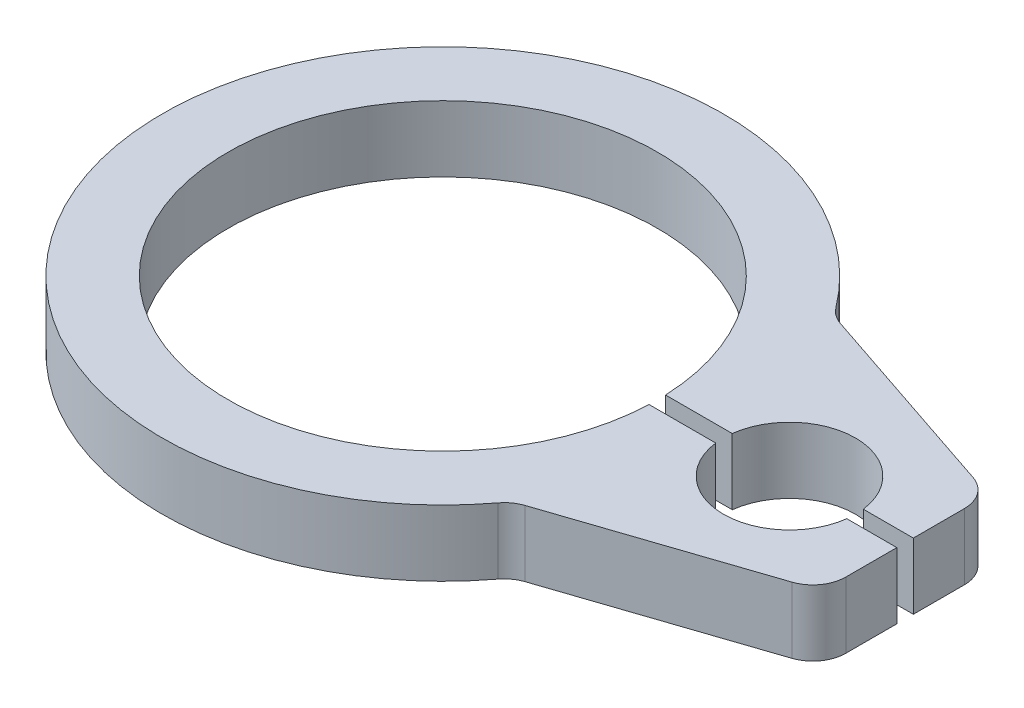
SolidWorks part; units mm, degrees
material "Plain Carbon Steel"
ref_plane "Front Plane" through (0, 0, 0) normal (0, 0, 1) x (1, 0, 0)
ref_plane "Top Plane" through (0, 0, 0) normal (0, 1, 0) x (1, 0, 0)
ref_plane "Right Plane" through (0, 0, 0) normal (1, 0, 0) x (0, 0, -1)
sketch "Sketch1" plane through (0, 0, 0) normal (0, 1, 0) x (1, 0, 0)
  line L0 (0, 0) -> (4.8502, 0) construction
  line L1 (1.3926, 0.975) -> (2.8, 0.5029)
  line L2 (2.8, 0.5029) -> (2.8, 0.05)
  line L3 (1.299, -0.05) -> (1.7031, -0.05)
  line L4 (1.299, 0.05) -> (1.7031, 0.05)
  line L5 (1.3926, -0.975) -> (2.8, -0.5029)
  line L6 (2.8, -0.05) -> (2.8, -0.5029)
  line L7 (0, -0.05) -> (4.8502, -0.05) construction
  line L8 (0, 0.05) -> (4.8502, 0.05) construction
  line L9 (2.4969, 0.05) -> (2.8, 0.05)
  line L10 (2.4969, -0.05) -> (2.8, -0.05)
  arc A0 (1.299, 0.05) -> (1.299, -0.05) centre (0, 0) ccw
  arc A1 (1.3926, 0.975) -> (1.3926, -0.975) centre (0, 0) ccw
  circle A2 centre (2.1, 0) radius 0.4
  point P13 (3.4222, 0)
  dimension "D1" = 2.6
  dimension "D2" = 3.4
  dimension "D8" = 0.8
  dimension "D3" = 2.8
  dimension "D4" = 0.8
  dimension "D7" = 2.1
  dimension "D5" = 0.05
  dimension "D6" = 0.05
extrude "Boss-Extrude1" add sketch "Sketch1" along normal blind 0.4 contours A2 L9 L2 L1 A1 L5 L6 L10 L3 A0 L4
fillet "Fillet1" radius 0.2 4 edges at (1.3926, 0.2, 0.975) (1.3926, 0.2, -0.975) (2.8, 0.2, 0.5029) (2.8, 0.2, -0.5029)
